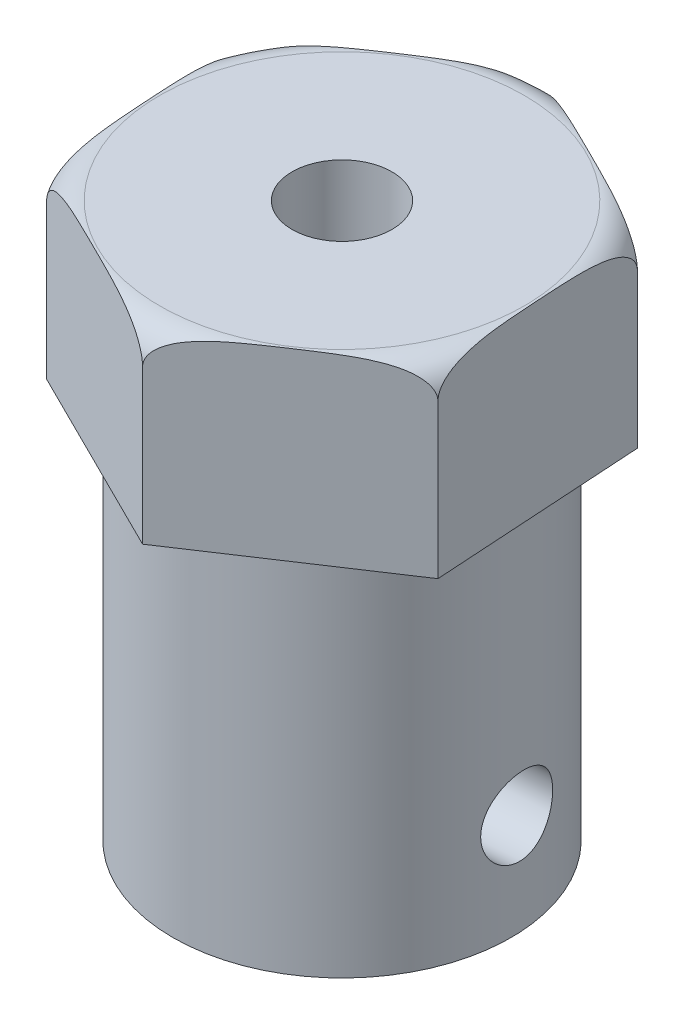
SolidWorks part; units mm, degrees
ref_plane "Front Plane" through (0, 0, 0) normal (0, 0, 1) x (1, 0, 0)
ref_plane "Top Plane" through (0, 0, 0) normal (0, 1, 0) x (1, 0, 0)
ref_plane "Right Plane" through (0, 0, 0) normal (1, 0, 0) x (0, 0, -1)
sketch "Sketch1" plane through (0, 0, 0) normal (0, 1, 0) x (1, 0, 0)
  line L0 (-15.5789, -4.4138) -> (-15.5789, -6.9138)
  circle A0 centre (-15.5789, -9.9138) radius 5.5
  circle A1 centre (-15.5789, -9.9138) radius 3
extrude "Boss-Extrude1" add sketch "Sketch1" along normal blind 12
sketch "Sketch2" plane through (0, 12, 0) normal (0, 1, 0) x (1, 0, 0)
  line L0 (-18.25, -15.2864) -> (-12.9077, -4.5412)
  line L1 (-15.1481, -16.8286) -> (-9.3751, -12.9982)
  line L2 (-9.3751, -12.9982) -> (-9.8058, -6.0834)
  line L3 (-9.8058, -6.0834) -> (-16.0096, -2.999)
  line L4 (-16.0096, -2.999) -> (-21.7826, -6.8295)
  line L5 (-21.7826, -6.8295) -> (-21.3519, -13.7443)
  line L6 (-21.3519, -13.7443) -> (-15.1481, -16.8286)
  circle A0 centre (-15.5789, -9.9138) radius 6 construction
extrude "Boss-Extrude2" add sketch "Sketch2" along normal blind 6 contours L4 L5 L6 L1 L2 L3
sketch "Sketch3" plane through (0, 18, 0) normal (0, 1, 0) x (1, 0, 0)
  line L0 (-18.8961, -4.9142) -> (-12.2616, -14.9134)
  line L1 (-16.0096, -2.999) -> (-21.7826, -6.8295) construction
  line L2 (-15.1481, -16.8286) -> (-9.3751, -12.9982) construction
  circle A0 centre (-15.5789, -9.9138) radius 1.625
extrude "Cut-Extrude1" cut sketch "Sketch3" against normal blind 17 contours L0 A0 | L0 A0
ref_plane "Plane1" through (-16.1338, 0, 1.0051) normal (-0.9981, 0, 0.0622) x (0.0622, 0, 0.9981)
sketch "Sketch5" plane through (-16.1338, 0, 1.0051) normal (-0.9981, 0, 0.0622) x (0.0622, 0, 0.9981)
  line L0 (15.8542, 18) -> (15.8542, 17)
  line L1 (15.8542, 18) -> (15.8542, 12) construction
  line L2 (15.8542, 18) -> (14.8542, 18)
  line L3 (12.3901, 18) -> (15.8542, 18) construction
  line L4 (8.926, 18) -> (8.926, 21.5845)
  line L5 (5.4619, 18) -> (12.3901, 18) construction
  arc A0 (14.8542, 18) -> (15.8542, 17) centre (14.8542, 17) cw
revolve "Cut-Revolve1" cut sketch "Sketch5" angle 360 about L4
sketch "Sketch6" plane through (-10.1454, 0, 0.632) normal (0.9981, 0, -0.0622) x (-0.0622, 0, -0.9981)
  line L0 (-8.926, 0) -> (-8.926, 2)
  line L1 (-14.426, 0) -> (-3.426, 0) construction
  line L2 (-8.926, 2) -> (-8.926, 4.5)
  circle A0 centre (-8.926, 3.25) radius 1.25
extrude "Cut-Extrude4" cut sketch "Sketch6" against normal blind 22 contours L2 A0 | L2 A0
